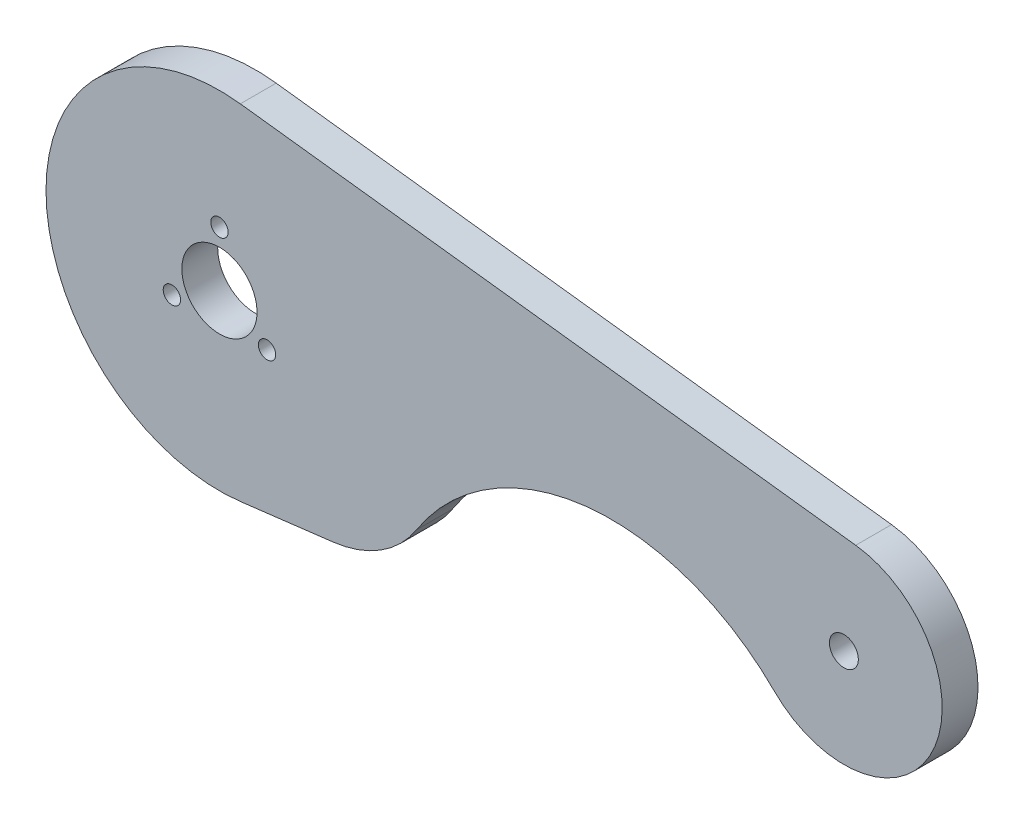
SolidWorks part; units mm, degrees
ref_plane "Front Plane" through (0, 0, 0) normal (0, 0, 1) x (1, 0, 0)
ref_plane "Top Plane" through (0, 0, 0) normal (0, 1, 0) x (1, 0, 0)
ref_plane "Right Plane" through (0, 0, 0) normal (1, 0, 0) x (0, 0, -1)
sketch "Sketch1" plane through (0, 0, 0) normal (0, 0, 1) x (1, 0, 0)
  line L0 (3.6111, -29.7819) -> (19.6687, -27.8349)
  line L1 (110.0463, 16.8764) -> (3.6111, 29.7819)
  circle A0 centre (108, 0) radius 2.5
  circle A1 centre (0, 0) radius 6.5
  circle A2 centre (0, 0) radius 27.5 construction
  arc A3 (96, -12.0416) -> (110.0463, 16.8764) centre (108, 0) ccw
  arc A4 (3.6111, 29.7819) -> (3.6111, -29.7819) centre (0, 0) ccw
  arc A8 (96, -12.0416) -> (34.0957, -18.7784) centre (67.7647, -40.3748) ccw
  arc A9 (34.0957, -18.7784) -> (19.6687, -27.8349) centre (17.2613, -7.9803) cw
  point P20 (99.8909, -18.1078)
  dimension "D1" = 13
  dimension "D2" = 108
  dimension "D3" = 5
  dimension "D4" = 30
  dimension "D5" = 17
  dimension "D6" = 20
  dimension "D7" = 40
  dimension "D8" = 12
extrude "Boss-Extrude1" add sketch "Sketch1" along normal blind 6.2 contours L1 A4 L0 A3 A0 A2
sketch "Sketch2" plane through (0, 0, 0) normal (0, 0, -1) x (-1, 0, 0)
  circle A0 centre (8.2272, -4.75) radius 1.5 construction
  circle A1 centre (-8.2272, -4.75) radius 1.5 construction
  circle A2 centre (0, 9.5) radius 1.5 construction
  circle A3 centre (8.2272, -4.75) radius 1.5
  circle A4 centre (-8.2272, -4.75) radius 1.5
  circle A5 centre (0, 9.5) radius 1.5
extrude "Cut-Extrude1" cut sketch "Sketch2" against normal up to next
